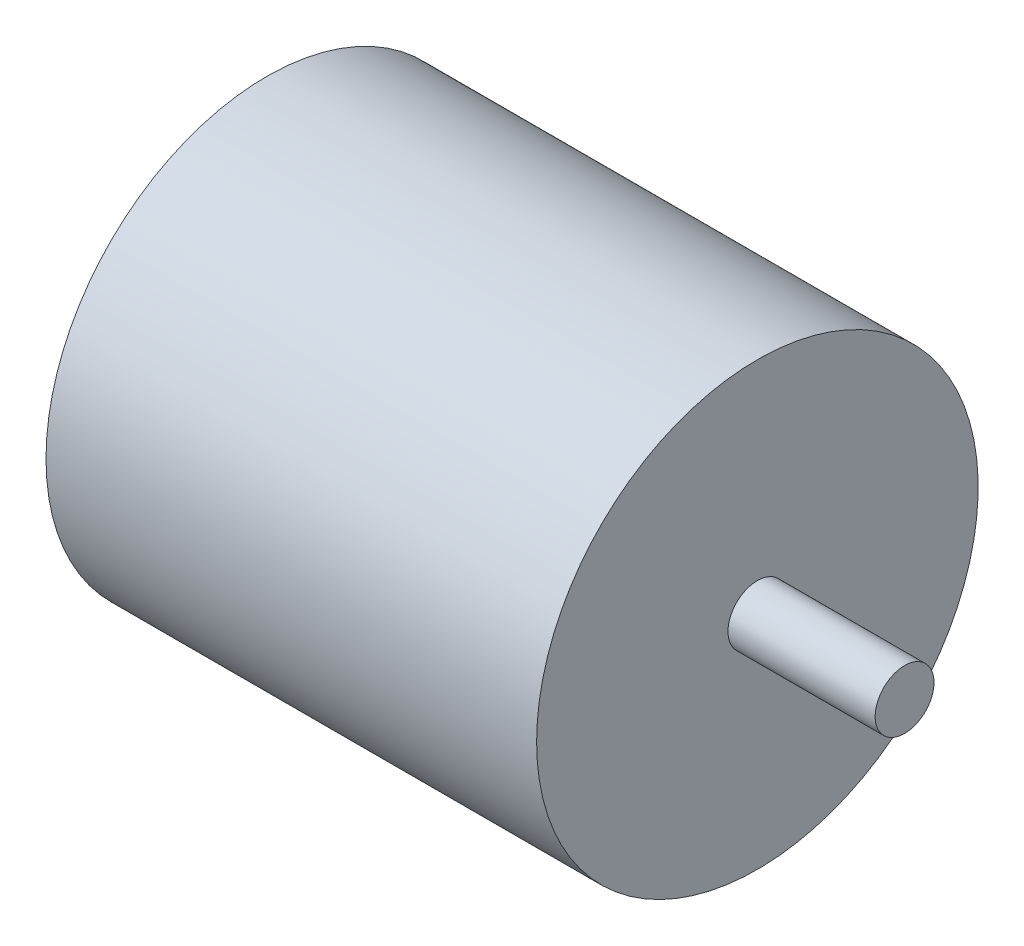
SolidWorks part; units mm, degrees
ref_plane "前视基准面" through (0, 0, 0) normal (0, 0, 1) x (1, 0, 0)
ref_plane "上视基准面" through (0, 0, 0) normal (0, 1, 0) x (1, 0, 0)
ref_plane "右视基准面" through (0, 0, 0) normal (1, 0, 0) x (0, 0, -1)
sketch "草图1" plane through (0, 0, 0) normal (1, 0, 0) x (0, 0, -1)
  circle A0 centre (0, 0) radius 3
extrude "凸台-拉伸1" add sketch "草图1" along normal blind 15
sketch "草图2" plane through (0, 0, 0) normal (-1, 0, 0) x (0, 0, 1)
  circle A0 centre (0, 0) radius 22.5
extrude "凸台-拉伸2" add sketch "草图2" along normal blind 50
